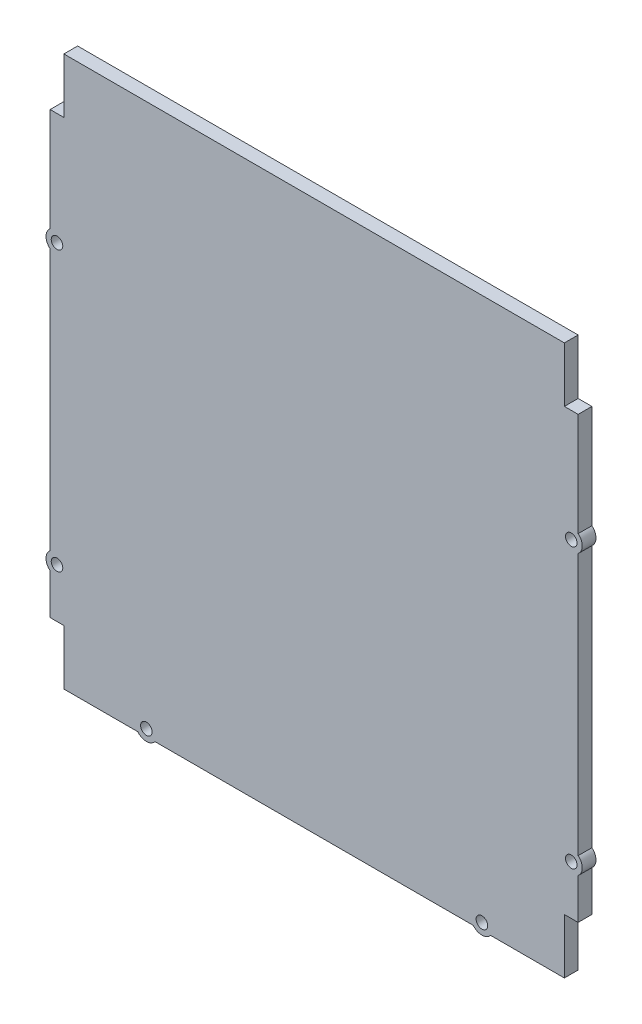
SolidWorks part; units mm, degrees
ref_plane "Front Plane" through (0, 0, 0) normal (0, 0, 1) x (1, 0, 0)
ref_plane "Top Plane" through (0, 0, 0) normal (0, 1, 0) x (1, 0, 0)
ref_plane "Right Plane" through (0, 0, 0) normal (1, 0, 0) x (0, 0, -1)
sketch "Sketch1" plane through (0, 0, 0) normal (0, 0, 1) x (1, 0, 0)
  line L0 (-182, 200) -> (-182, 180)
  line L1 (-182, 180) -> (-187, 180)
  line L2 (-187, 180) -> (-187, 20)
  line L3 (-187, 20) -> (-182, 20)
  line L4 (-182, 20) -> (-182, 0)
  line L5 (-182, 0) -> (0, 0)
  line L6 (0, 0) -> (0, 20)
  line L7 (0, 20) -> (5, 20)
  line L8 (5, 20) -> (5, 180)
  line L9 (5, 180) -> (0, 180)
  line L10 (0, 180) -> (0, 200)
  line L11 (0, 200) -> (-182, 200)
  dimension "D1" = 182
  dimension "D2" = 160
  dimension "D3" = 20
  dimension "D4" = 20
  dimension "D5" = 5
  dimension "D6" = 5
  dimension "D7" = 5
  dimension "D8" = 5
  dimension "D9" = 20
  dimension "D10" = 20
extrude "Boss-Extrude1" add sketch "Sketch1" along normal blind 5
sketch "Sketch2" plane through (0, 0, 0) normal (0, 0, -1) x (-1, 0, 0)
  line L0 (0, 200) -> (182, 200) construction
  line L1 (-5, 20) -> (-5, 180) construction
  line L3 (182, 0) -> (0, 0) construction
  line L4 (91, 200) -> (91, 0) construction
  circle A0 centre (-2.5, 139.3) radius 2.1
  circle A1 centre (-2.5, 37.9) radius 2.1
  circle A2 centre (184.5, 37.9) radius 2.1
  circle A3 centre (184.5, 139.3) radius 2.1
  dimension "D1" = 4.2
  dimension "D3" = 2.5
  dimension "D4" = 4.2
  dimension "D5" = 2.5
  dimension "D6" = 37.9
  dimension "D2" = 60.7
extrude "Cut-Extrude1" cut sketch "Sketch2" against normal blind 10
sketch "Sketch3" plane through (0, 0, 0) normal (0, 0, -1) x (-1, 0, 0)
  line L0 (-5, 20) -> (-5, 180) construction
  line L1 (-5, 136.1775) -> (-5, 142.4225)
  arc A0 (-5, 142.4225) -> (-5, 136.1775) centre (-2.5, 139.3) ccw
  dimension "D1" = 8
extrude "Boss-Extrude2" add sketch "Sketch3" against normal blind 5
sketch "Sketch4" plane through (0, 0, 0) normal (0, 0, -1) x (-1, 0, 0)
  line L0 (-5, 20) -> (-5, 136.1775) construction
  line L1 (-5, 34.7775) -> (-5, 41.0225)
  arc A0 (-5, 41.0225) -> (-5, 34.7775) centre (-2.5, 37.9) ccw
extrude "Boss-Extrude3" add sketch "Sketch4" against normal blind 5
ref_plane "Plane1" through (-91, 0, 0) normal (-1, 0, 0) x (0, 0, 1)
mirror "Mirror1" about plane through (-91, 0, 0) normal (-1, 0, 0) of "Boss-Extrude2", "Boss-Extrude3"
sketch "Sketch5" plane through (0, 0, 0) normal (0, 0, -1) x (-1, 0, 0)
  line L0 (182, 0) -> (0, 0) construction
  line L1 (182, 20) -> (182, 0) construction
  line L2 (0, 0) -> (0, 20) construction
  circle A0 centre (30, 2.5) radius 2.1
  circle A1 centre (152, 2.5) radius 2.1
  dimension "D1" = 2.5
  dimension "D3" = 30
  dimension "D2" = 2.5
  dimension "D4" = 30
extrude "Cut-Extrude2" cut sketch "Sketch5" against normal blind 5
sketch "Sketch6" plane through (0, 0, 0) normal (0, 0, -1) x (-1, 0, 0)
  line L0 (182, 0) -> (0, 0) construction
  line L1 (155.1225, 0) -> (148.8775, 0)
  line L2 (33.1225, 0) -> (26.8775, 0)
  arc A0 (26.8775, 0) -> (33.1225, 0) centre (30, 2.5) ccw
  arc A1 (148.8775, 0) -> (155.1225, 0) centre (152, 2.5) ccw
extrude "Boss-Extrude4" add sketch "Sketch6" against normal blind 5
